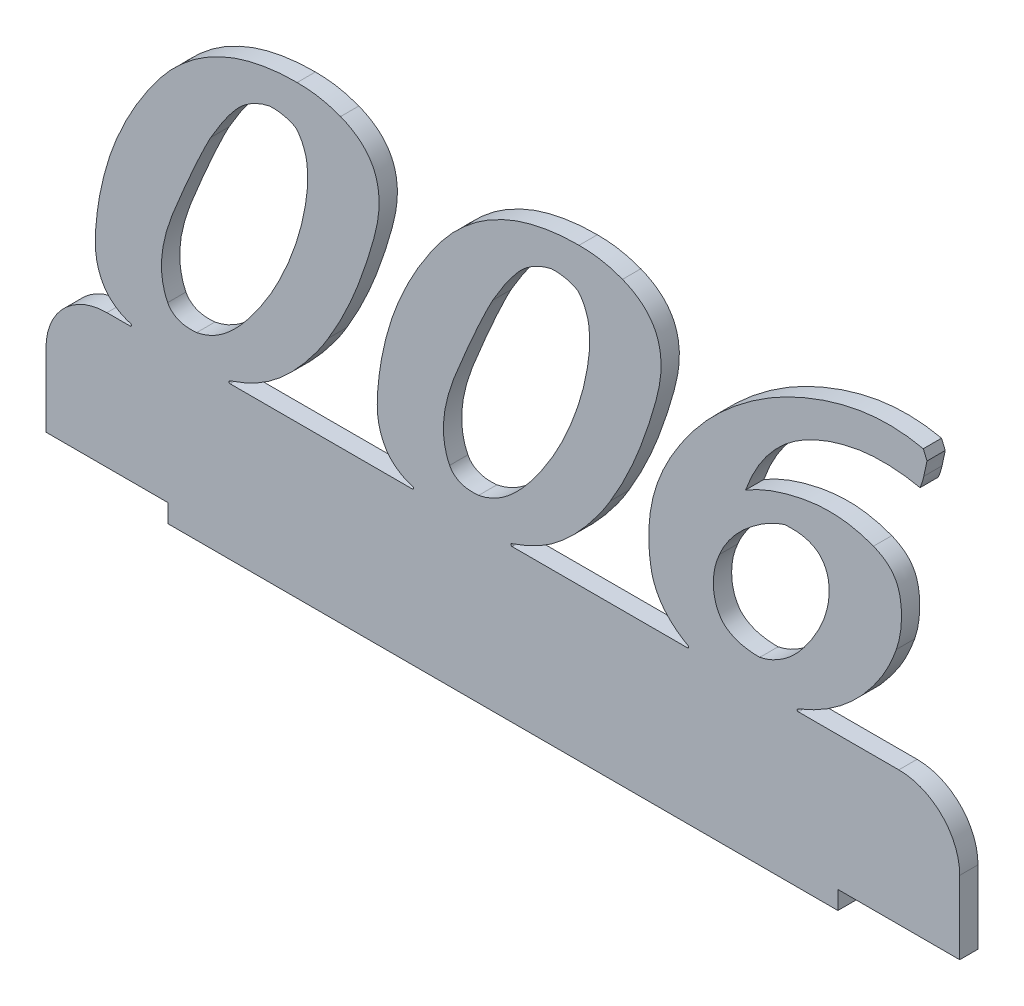
SolidWorks part; units mm, degrees
ref_plane "Front Plane" through (0, 0, 0) normal (0, 0, 1) x (1, 0, 0)
ref_plane "Top Plane" through (0, 0, 0) normal (0, 1, 0) x (1, 0, 0)
ref_plane "Right Plane" through (0, 0, 0) normal (1, 0, 0) x (0, 0, -1)
sketch "Sketch1" plane through (0, 0, 0) normal (0, 0, 1) x (1, 0, 0)
  line L0 (0, 20) -> (150, 20) construction
  line L1 (122.4075, 22) -> (150, 22)
  line L2 (0, 22) -> (0, 0)
  line L3 (0, 0) -> (20, 0)
  line L4 (150, 22) -> (150, 0)
  line L5 (0, 22) -> (15.3114, 22)
  line L6 (144.0185, 69.6645) -> (144.6244, 68.218)
  line L7 (28.9202, 22) -> (61.5975, 22)
  line L8 (75.2064, 22) -> (106.288, 22)
  line L11 (130, 0) -> (150, 0)
  line L13 (20, 0) -> (20, -3)
  line L14 (20, -3) -> (130, -3)
  line L15 (130, 0) -> (130, -3)
  spline S0 degree 3 poles (41.0865, 63.7223) (40.4853, 64.1318) (39.02, 64.638) (37.4822, 64.7653) (36.669, 64.7192) knots 0 0 0 0 0.469699 1 1 1 1
  spline S1 degree 3 poles (36.669, 64.7192) (35.5243, 64.4785) (33.9063, 63.801) (32.0179, 62.4234) (29.71, 59.8453) (28.1763, 57.3938) (27.0326, 55.415) knots 0 0 0 0 0.25259 0.375811 0.50377 1 1 1 1
  spline S2 degree 3 poles (27.0326, 55.415) (26.5763, 54.617) (25.9781, 53.3004) (25.0866, 51.4814) (24.3731, 49.8998) (23.6087, 48.1806) (22.8082, 46.3139) (21.9516, 44.3176) (21.0796, 42.2293) (20.2866, 40.1311) (19.6549, 38.1038) (19.2141, 36.1967) (18.9712, 34.4037) (18.9239, 32.7244) (19.1256, 30.6987) (19.5451, 29.275) (19.9763, 28.4213) knots 0 0 0 0 0.095871 0.150957 0.21155 0.277044 0.347448 0.42366 0.503899 0.583776 0.657815 0.725493 0.787949 0.846481 0.90051 1 1 1 1
  spline S3 degree 3 poles (19.9763, 28.4213) (20.3347, 27.6783) (21.8342, 26.471) (23.7471, 26.4544) (24.7261, 26.5253) knots 0 0 0 0 0.446154 1 1 1 1
  spline S4 degree 3 poles (24.7261, 26.5253) (26.1836, 26.7996) (28.3402, 27.8181) (30.8725, 29.9858) (32.823, 32.143) (34.6898, 34.6285) (36.4513, 37.3025) (38.0417, 40.129) (39.4363, 43.0853) (40.6344, 46.1023) (41.626, 49.1143) (42.3446, 52.1028) (42.8492, 54.9934) (43.0188, 57.6952) (42.8169, 60.7257) (41.9421, 62.7143) (41.0865, 63.7223) knots 0 0 0 0 0.099523 0.157976 0.224341 0.295662 0.367825 0.440561 0.514606 0.588508 0.65979 0.72866 0.796042 0.857776 0.911265 1 1 1 1
  spline S5 degree 3 poles (15.3114, 22) (14.8498, 22.1134) (13.8656, 22.3849) (12.4155, 22.8957) (11.1092, 23.7455) (9.9992, 24.7646) (9.1693, 26.0418) (8.5638, 27.5134) (8.0102, 29.8782) (8.0798, 31.7979) (8.1702, 33.1125) knots 0.448243 0.448243 0.448243 0.448243 0.501388 0.5623 0.61932 0.674488 0.729675 0.788153 0.851799 1 1 1 1
  spline S6 degree 3 poles (8.1702, 33.1125) (8.3371, 35.3406) (8.8263, 38.6661) (9.9557, 43.0029) (11.0185, 46.2123) (12.3731, 49.3456) (13.9111, 52.4515) (15.7189, 55.4946) (17.726, 58.4617) (19.9235, 61.2511) (22.3978, 63.6699) (25.04, 65.7575) (27.9202, 67.4049) (30.9557, 68.7528) (35.3781, 69.9751) (38.8569, 70.3598) (41.2233, 70.329) knots 0 0 0 0 0.122246 0.183381 0.245051 0.307032 0.370011 0.434579 0.500535 0.565958 0.62848 0.689454 0.749684 0.809559 0.870725 1 1 1 1
  spline S7 degree 3 poles (41.2233, 70.329) (42.4836, 70.3186) (44.9264, 70.1751) (47.2666, 69.4652) (48.3578, 69.0585) knots 0 0 0 0 0.519885 1 1 1 1
  spline S8 degree 3 poles (48.3578, 69.0585) (49.6254, 68.5432) (51.4204, 67.5499) (53.1597, 65.567) (54.0693, 63.8935) (54.5845, 61.9886) (54.7499, 59.8715) (54.5567, 57.5407) (53.8073, 54.2013) (52.5288, 50.0349) (50.2276, 43.7313) (48.0307, 39.3051) (46.3641, 36.5526) knots 0 0 0 0 0.111906 0.162582 0.212593 0.265416 0.321766 0.384451 0.454781 0.599581 0.738515 1 1 1 1
  spline S9 degree 3 poles (46.3641, 36.5526) (45.2726, 34.6954) (43.4023, 32.125) (40.653, 29.002) (38.4843, 26.9327) (36.1018, 25.125) (33.4221, 23.6293) (30.9881, 22.6398) (29.4483, 22.1529) (28.9202, 22) knots 0 0 0 0 0.25786 0.380114 0.498337 0.616577 0.737567 0.865048 0.930899 0.930899 0.930899 0.930899
  spline S10 degree 3 poles (87.3727, 63.7223) (86.7714, 64.1318) (85.3061, 64.638) (83.7683, 64.7653) (82.9552, 64.7192) knots 0 0 0 0 0.469699 1 1 1 1
  spline S11 degree 3 poles (82.9552, 64.7192) (81.8105, 64.4785) (80.1924, 63.801) (78.304, 62.4234) (75.9961, 59.8453) (74.4624, 57.3938) (73.3187, 55.415) knots 0 0 0 0 0.25259 0.375811 0.50377 1 1 1 1
  spline S12 degree 3 poles (73.3187, 55.415) (72.8625, 54.617) (72.2642, 53.3004) (71.3727, 51.4814) (70.6593, 49.8998) (69.8949, 48.1806) (69.0944, 46.3139) (68.2378, 44.3176) (67.3657, 42.2293) (66.5727, 40.1311) (65.9411, 38.1038) (65.5003, 36.1967) (65.2574, 34.4037) (65.2101, 32.7244) (65.4118, 30.6987) (65.8313, 29.275) (66.2624, 28.4213) knots 0 0 0 0 0.095871 0.150957 0.21155 0.277044 0.347448 0.42366 0.503899 0.583776 0.657815 0.725493 0.787949 0.846481 0.90051 1 1 1 1
  spline S13 degree 3 poles (66.2624, 28.4213) (66.6209, 27.6783) (68.1204, 26.471) (70.0333, 26.4544) (71.0122, 26.5253) knots 0 0 0 0 0.446154 1 1 1 1
  spline S14 degree 3 poles (71.0122, 26.5253) (72.4698, 26.7996) (74.6264, 27.8181) (77.1587, 29.9858) (79.1091, 32.143) (80.9759, 34.6285) (82.7375, 37.3025) (84.3279, 40.129) (85.7224, 43.0853) (86.9206, 46.1023) (87.9121, 49.1143) (88.6308, 52.1028) (89.1353, 54.9934) (89.305, 57.6952) (89.1031, 60.7257) (88.2282, 62.7143) (87.3727, 63.7223) knots 0 0 0 0 0.099523 0.157976 0.224341 0.295662 0.367825 0.440561 0.514606 0.588508 0.65979 0.72866 0.796042 0.857776 0.911265 1 1 1 1
  spline S15 degree 3 poles (61.5975, 22) (61.136, 22.1134) (60.1518, 22.3849) (58.7017, 22.8957) (57.3953, 23.7455) (56.2853, 24.7646) (55.4555, 26.0418) (54.85, 27.5134) (54.2964, 29.8782) (54.366, 31.7979) (54.4563, 33.1125) knots 0.448243 0.448243 0.448243 0.448243 0.501388 0.5623 0.61932 0.674488 0.729675 0.788153 0.851799 1 1 1 1
  spline S16 degree 3 poles (54.4563, 33.1125) (54.6233, 35.3406) (55.1125, 38.6661) (56.2418, 43.0029) (57.3047, 46.2123) (58.6593, 49.3456) (60.1973, 52.4515) (62.005, 55.4946) (64.0121, 58.4617) (66.2097, 61.2511) (68.6839, 63.6699) (71.3262, 65.7575) (74.2064, 67.4049) (77.2419, 68.7528) (81.6643, 69.9751) (85.143, 70.3598) (87.5095, 70.329) knots 0 0 0 0 0.122246 0.183381 0.245051 0.307032 0.370011 0.434579 0.500535 0.565958 0.62848 0.689454 0.749684 0.809559 0.870725 1 1 1 1
  spline S17 degree 3 poles (87.5095, 70.329) (88.7697, 70.3186) (91.2126, 70.1751) (93.5527, 69.4652) (94.644, 69.0585) knots 0 0 0 0 0.519885 1 1 1 1
  spline S18 degree 3 poles (94.644, 69.0585) (95.9115, 68.5432) (97.7066, 67.5499) (99.4459, 65.567) (100.3554, 63.8935) (100.8707, 61.9886) (101.036, 59.8715) (100.8429, 57.5407) (100.0935, 54.2013) (98.815, 50.0349) (96.5138, 43.7313) (94.3169, 39.3051) (92.6502, 36.5526) knots 0 0 0 0 0.111906 0.162582 0.212593 0.265416 0.321766 0.384451 0.454781 0.599581 0.738515 1 1 1 1
  spline S19 degree 3 poles (92.6502, 36.5526) (91.5588, 34.6954) (89.6885, 32.125) (86.9391, 29.002) (84.7704, 26.9327) (82.388, 25.125) (79.7083, 23.6293) (77.2743, 22.6398) (75.7345, 22.1529) (75.2064, 22) knots 0 0 0 0 0.25786 0.380114 0.498337 0.616577 0.737567 0.865048 0.930899 0.930899 0.930899 0.930899
  spline S20 degree 3 poles (121.2664, 47.4987) (120.2079, 47.1815) (118.6519, 46.4409) (116.6582, 45.148) (115.1238, 43.9568) (113.6774, 42.6266) (112.0312, 40.682) (111.048, 39.0721) (110.5744, 37.9209) knots 0 0 0 0 0.224054 0.348681 0.482825 0.618797 0.747604 1 1 1 1
  spline S21 degree 3 poles (110.5744, 37.9209) (109.9833, 36.6921) (109.5088, 34.724) (109.5679, 32.0827) (109.949, 30.5226) (110.4857, 29.3786) (111.0202, 28.6091) (111.7205, 27.978) (112.5568, 27.4767) (113.5082, 27.0464) (115.0645, 26.6951) (116.3074, 26.5722) (117.1811, 26.5839) knots 0 0 0 0 0.248209 0.363825 0.480559 0.538643 0.594178 0.650677 0.709525 0.771943 0.840712 1 1 1 1
  spline S22 degree 3 poles (117.1811, 26.5839) (118.6827, 26.8844) (120.8215, 27.9709) (123.2996, 30.1489) (124.983, 32.2774) (126.4712, 34.5556) (127.9402, 37.5441) (128.5107, 39.8876) (128.5767, 41.4197) knots 0 0 0 0 0.229647 0.356932 0.4972 0.639278 0.768609 1 1 1 1
  spline S23 degree 3 poles (128.5767, 41.4197) (128.5852, 42.3768) (128.4471, 43.7912) (127.6309, 45.3789) (126.8283, 46.3067) (125.7434, 46.9528) (123.8962, 47.5649) (122.3351, 47.5594) (121.2664, 47.4987) knots 0 0 0 0 0.260935 0.371909 0.477859 0.587726 0.708482 1 1 1 1
  spline S24 degree 3 poles (139.601, 38.9178) (138.9989, 37.2283) (137.4658, 33.8938) (135.212, 30.9993) (133.9911, 29.6136) knots 0 0 0 0 0.492481 1 1 1 1
  spline S25 degree 3 poles (133.9911, 29.6136) (132.2365, 27.7136) (129.221, 25.1734) (125.0648, 23.0255) (123.1321, 22.2558) (122.4075, 22) knots 0 0 0 0 0.246096 0.370528 0.443538 0.443538 0.443538 0.443538
  spline S26 degree 3 poles (105.2968, 22.4205) (104.4862, 22.888) (103.3387, 23.6548) (102.0416, 24.9019) (101.2128, 25.8783) (100.5278, 26.9384) (99.7863, 28.4589) (99.4112, 29.6813) (99.2961, 30.5323) knots 0 0 0 0 0.268967 0.393275 0.515369 0.63569 0.754431 1 1 1 1
  spline S27 degree 3 poles (99.2961, 30.5323) (99.0825, 31.896) (98.8888, 33.9595) (98.9902, 36.7037) (99.2556, 38.7343) (99.6556, 40.7449) (100.2538, 42.7368) (101.0185, 44.7072) (102.2456, 47.3117) (104.1044, 50.4237) (106.6665, 53.9347) (109.5816, 57.1891) (112.8391, 60.1353) (116.3544, 62.7971) (120.0867, 65.1109) (124.0287, 67.0307) (128.0919, 68.5876) (132.205, 69.716) (137.5324, 70.4847) (141.5018, 70.2188) (144.0185, 69.6645) knots 0 0 0 0 0.061189 0.09153 0.121507 0.15186 0.182283 0.213545 0.24545 0.309778 0.373827 0.437828 0.503032 0.568174 0.633001 0.697311 0.762199 0.825587 0.885942 1 1 1 1
  spline S28 degree 3 poles (144.6244, 68.218) (144.4874, 67.6201) (144.3105, 66.8058) (144.1457, 65.989) (144.0967, 65.7747) knots 0 0 0 0 0.73621 1 1 1 1
  spline S29 degree 2 poles (144.0967, 65.7747) (143.8798, 64.7892) (143.4907, 63.8591) knots 0 0 0 1 1 1
  spline S30 degree 3 poles (143.4907, 63.8591) (142.0433, 64.1695) (139.8526, 64.4847) (136.9284, 64.5268) (134.7696, 64.423) (132.6321, 64.1021) (130.5186, 63.6059) (128.4132, 62.9685) (126.3649, 62.1269) (124.3867, 61.1483) (122.5584, 59.9594) (120.8677, 58.6182) (119.3557, 57.0691) (117.9788, 55.3664) (116.3377, 52.8049) (115.3685, 50.6978) (114.8551, 49.2188) knots 0 0 0 0 0.125883 0.187368 0.24838 0.309394 0.37079 0.432804 0.496156 0.55882 0.620115 0.68118 0.741882 0.803725 0.867017 1 1 1 1
  spline S31 degree 3 poles (114.8551, 49.2188) (116.3894, 50.1054) (118.8472, 51.231) (122.3331, 52.2487) (125.0743, 52.827) (127.8534, 53.1066) (131.5117, 53.0146) (134.1679, 52.3633) (135.8481, 51.7207) knots 0 0 0 0 0.243539 0.369641 0.498564 0.628138 0.752678 1 1 1 1
  spline S32 degree 3 poles (135.8481, 51.7207) (136.9993, 51.248) (138.6723, 50.2345) (139.909, 48.0437) (140.3379, 46.2329) (140.479, 44.3536) (140.3677, 41.8764) (140.012, 40.065) (139.601, 38.9178) knots 0 0 0 0 0.25561 0.374245 0.499505 0.629042 0.754309 1 1 1 1
  spline S33 degree 2 poles (106.288, 22) (105.7869, 22.1959) (105.2968, 22.4205) knots 0.965898 0.965898 0.965898 1 1 1
  dimension "D1" = 150
  dimension "D2" = 3
  dimension "D3" = 20
  dimension "D4" = 20
  dimension "D5" = 20
extrude "Boss-Extrude1" add sketch "Sketch1" along normal blind 3
fillet "Fillet1" radius 10 2 edges at (0, 22, 1.5) (150, 22, 1.5)
fillet "Fillet2" radius 0.2 6 edges at (28.9202, 22, 1.5) (75.2064, 22, 1.5) (122.4075, 22, 1.5) (106.288, 22, 1.5) (61.5975, 22, 1.5) (15.3114, 22, 1.5)
